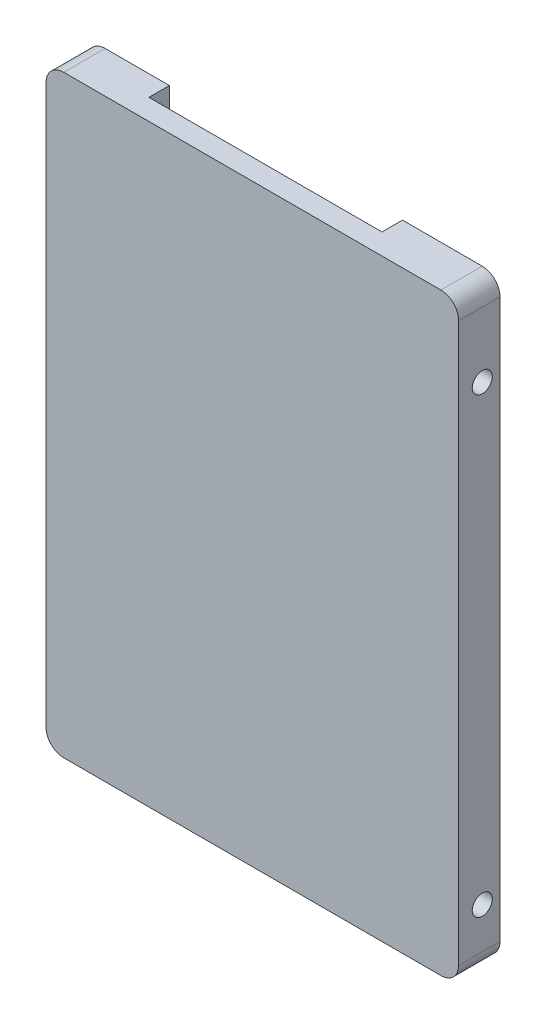
SolidWorks part; units mm, degrees
ref_plane "Front Plane" through (0, 0, 0) normal (0, 0, 1) x (1, 0, 0)
ref_plane "Top Plane" through (0, 0, 0) normal (0, 1, 0) x (1, 0, 0)
ref_plane "Right Plane" through (0, 0, 0) normal (1, 0, 0) x (0, 0, -1)
sketch "Sketch1" plane through (0, 0, 0) normal (0, 0, 1) x (1, 0, 0)
  line L1 (0, 0) -> (69.85, 0)
  line L2 (0, 0) -> (0, 100.5)
  line L3 (0, 100.5) -> (69.85, 100.5)
  line L4 (69.85, 0) -> (69.85, 100.5)
  dimension "D1" = 69.85
  dimension "D2" = 100.5
extrude "Boss-Extrude1" add sketch "Sketch1" along normal blind 7
fillet "Fillet1" radius 3 4 edges at (69.85, 0, 3.5) (0, 0, 3.5) (0, 100.5, 3.5) (69.85, 100.5, 3.5)
sketch "Sketch2" plane through (0, 0, 0) normal (0, 0, 1) x (1, 0, 0)
  line L0 (4.07, 86.5) -> (65.78, 86.5) construction
  line L1 (65.78, 86.5) -> (65.78, 9.9) construction
  line L2 (65.78, 9.9) -> (4.07, 9.9) construction
  line L3 (4.07, 9.9) -> (4.07, 86.5) construction
  line L4 (66.85, 100.5) -> (3, 100.5) construction
  line L5 (34.925, 9.9) -> (34.925, 0) construction
  line L6 (3, 0) -> (66.85, 0) construction
  dimension "D1" = 61.71
  dimension "D2" = 90.6
  dimension "D3" = 14
hole_wizard "M3 Clearance Hole1" positions "3DSketch1" profile "Sketch3" hole size "M3" standard "ANSI Metric"
sketch3d "3DSketch1"
  point P0 (4.07, 86.5, 0)
  point P3 (65.78, 86.5, 0)
  point P6 (65.78, 9.9, 0)
  point P9 (4.07, 9.9, 0)
sketch "Sketch3" plane through (4.07, 86.5, 0) normal (1, 0, 0) x (0, 1, 0)
  line L0 (0, 0) -> (0, 3.0215)
  line L1 (0, 3.0215) -> (1.7, 2)
  line L2 (1.7, 2) -> (1.7, 0)
  line L5 (1.7, 0) -> (0, 0)
  line L10 (0, 3.0215) -> (-1.7, 2) construction
  line L11 (0, -6.35) -> (0, 107.95) construction
  dimension "Hole Dia." = 3.4
  dimension "Hole Depth" = 2
  dimension "Drill Angle" = 118
sketch "Sketch4" plane through (0, 0, 0) normal (-1, 0, 0) x (0, 0, 1)
  line L0 (0, 97.5) -> (0, 3) construction
  line L2 (3, 86.5) -> (3, 9.9) construction
  line L3 (3, 86.5) -> (3, 100.5) construction
  line L4 (0, 100.5) -> (7, 100.5) construction
  dimension "D1" = 3
  dimension "D2" = 14
  dimension "D3" = 90.6
hole_wizard "M3 Clearance Hole2" positions "3DSketch2" profile "Sketch5" hole size "M3" standard "ANSI Metric" end condition through all
sketch3d "3DSketch2"
  point P0 (0, 86.5, 3)
  point P3 (0, 9.9, 3)
sketch "Sketch5" plane through (0, 86.5, 3) normal (0, 1, 0) x (0, 0, 1)
  line L0 (0, 0) -> (0, 69.85)
  line L1 (0, 69.85) -> (1.7, 69.85)
  line L2 (1.7, 69.85) -> (1.7, 0)
  line L5 (1.7, 0) -> (0, 0)
  line L11 (0, -6.35) -> (0, 107.95) construction
  dimension "Thru Hole Dia." = 3.4
  dimension "Thru Hole Depth" = 69.85
sketch "Sketch6" plane through (0, 100.5, 0) normal (0, 1, 0) x (1, 0, 0)
  line L5 (66.85, 0) -> (3, 0) construction
  line L6 (53.3383, 0) -> (13.8838, 0)
  line L7 (53.3383, 0) -> (53.3383, -3.4664)
  line L8 (53.3383, -3.4664) -> (13.8838, -3.4664)
  line L9 (13.8838, 0) -> (13.8838, -3.4664)
extrude "Cut-Extrude1" cut sketch "Sketch6" against normal blind 5
